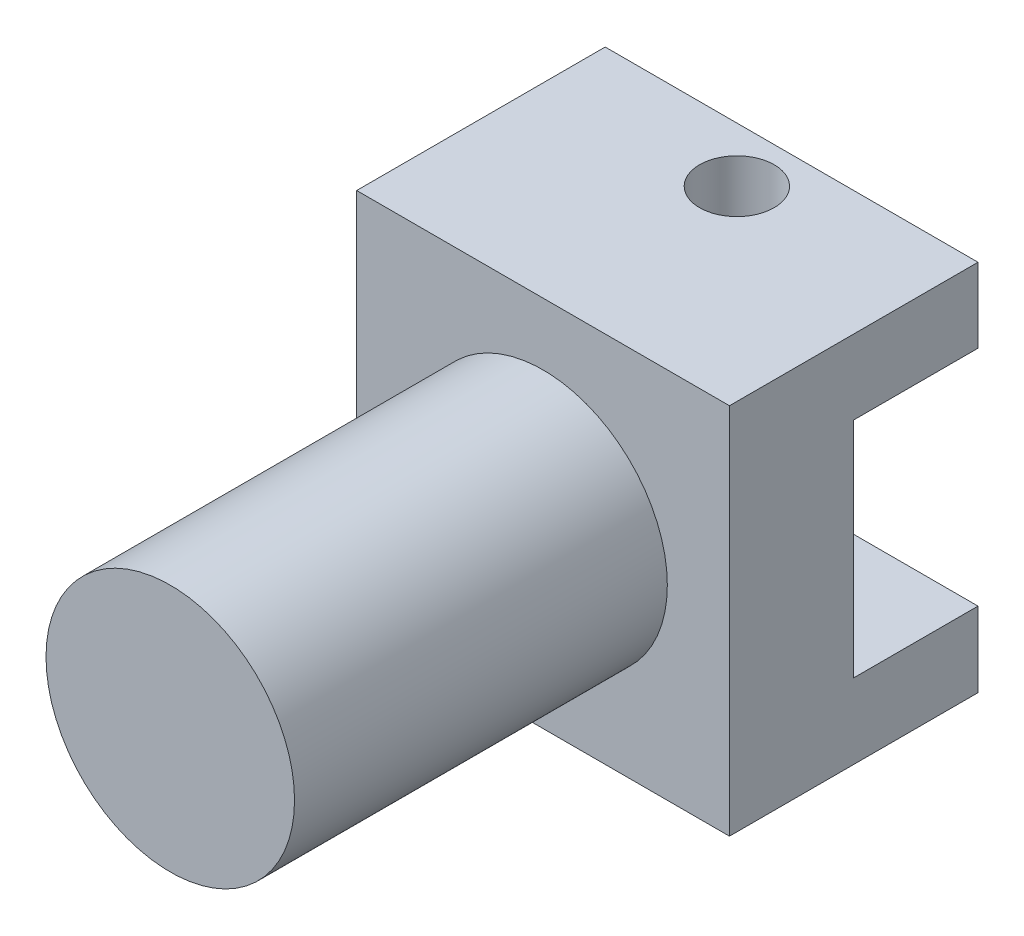
SolidWorks part; units mm, degrees
material "ABS"
ref_plane "Front Plane" through (0, 0, 0) normal (0, 0, 1) x (1, 0, 0)
ref_plane "Top Plane" through (0, 0, 0) normal (0, 1, 0) x (1, 0, 0)
ref_plane "Right Plane" through (0, 0, 0) normal (1, 0, 0) x (0, 0, -1)
sketch "Sketch5" plane through (0, 0, 0) normal (0, 0, 1) x (1, 0, 0)
  line L1 (0, 0) -> (76.2, 0)
  line L2 (0, 0) -> (0, 76.2)
  line L3 (0, 76.2) -> (76.2, 76.2)
  line L4 (76.2, 0) -> (76.2, 76.2)
  dimension "D1" = 76.2
  dimension "D2" = 76.2
extrude "Boss-Extrude3" add sketch "Sketch5" along normal blind 25.4
sketch "Sketch6" plane through (0, 0, 25.4) normal (0, 0, 1) x (1, 0, 0)
  line L0 (38.1, 76.2) -> (38.1, -16.489)
  line L1 (76.2, 76.2) -> (0, 76.2) construction
  line L2 (0, 38.1) -> (76.2, 38.1)
  line L3 (0, 76.2) -> (0, 0) construction
  line L4 (76.2, 0) -> (76.2, 76.2) construction
  circle A0 centre (38.1, 38.1) radius 25.4
extrude "Boss-Extrude4" add sketch "Sketch6" along normal blind 76.2 contours L2 A0 L0 | L0 A0 L2 | L2 A0 L0 | L0 A0 L2
sketch "Sketch7" plane through (0, 0, 0) normal (0, 0, -1) x (-1, 0, 0)
  line L5 (-38.1, 76.2) -> (-38.1, -4.3404)
  line L6 (0, 76.2) -> (0, 0) construction
  line L7 (22.2449, 35.9298) -> (-83.5245, 35.9298)
  line L8 (-76.2, 76.2) -> (0, 76.2)
  line L9 (-76.2, 76.2) -> (-76.2, 60.978)
  line L10 (-76.2, 60.978) -> (0, 60.978)
  line L11 (0, 76.2) -> (0, 60.978)
  line L13 (-76.2, 0) -> (0, 0)
  line L14 (-76.2, 0) -> (-76.2, 15.3325)
  line L15 (-76.2, 15.3325) -> (0, 15.3325)
  line L16 (0, 0) -> (0, 15.3325)
  line M6 (0, 0) -> (0, 76.2)
  line M7 (0, 76.2) -> (-76.2, 76.2)
  line M8 (-76.2, 76.2) -> (-76.2, 0)
  line M9 (-76.2, 0) -> (0, 0)
extrude "Boss-Extrude5" add sketch "Sketch7" along normal blind 25.4 contours L10 L5 M8 M7 | L5 L10 M6 M7 | L15 L5 M8 M9 | L15 L5 M9 M6
sketch "Sketch8" plane through (0, 0, 0) normal (0, -1, 0) x (1, 0, 0)
  circle A0 centre (38.1, -14.2137) radius 7.62
extrude "Cut-Extrude1" cut sketch "Sketch8" against normal through all
